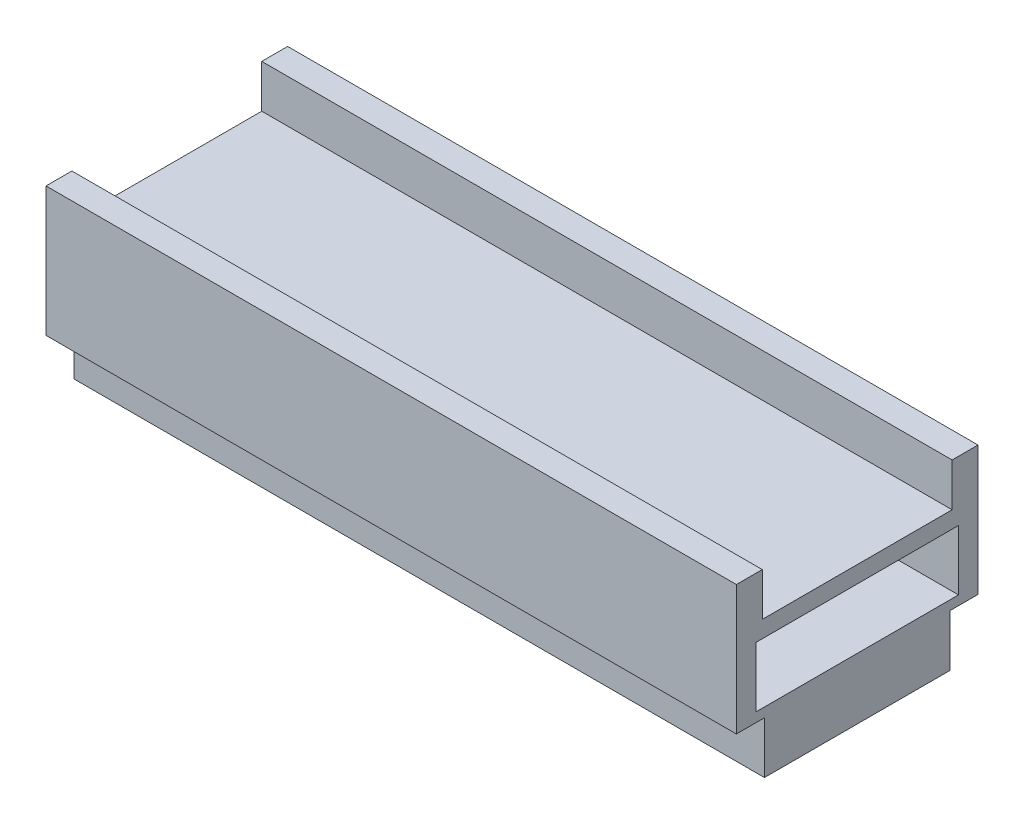
SolidWorks part; units mm, degrees
ref_plane "Front Plane" through (0, 0, 0) normal (0, 0, 1) x (1, 0, 0)
ref_plane "Top Plane" through (0, 0, 0) normal (0, 1, 0) x (1, 0, 0)
ref_plane "Right Plane" through (0, 0, 0) normal (1, 0, 0) x (0, 0, -1)
sketch "Sketch1" plane through (0, 0, 0) normal (0, 1, 0) x (1, 0, 0)
  line L1 (-40, 10.75) -> (40, 10.75)
  line L2 (-40, 10.75) -> (-40, -10.75)
  line L3 (-40, -10.75) -> (40, -10.75)
  line L4 (40, 10.75) -> (40, -10.75)
  line L5 (-40, 10.75) -> (40, -10.75) construction
  line L6 (-40, -10.75) -> (40, 10.75) construction
  point P0 (0, 0)
  dimension "D1" = 21.5
  dimension "D2" = 80
extrude "Boss-Extrude1" add sketch "Sketch1" along normal blind 6
sketch "Sketch2" plane through (0, 6, 0) normal (0, 1, 0) x (1, 0, 0)
  line L1 (-40, 14) -> (40, 14)
  line L2 (-40, 14) -> (-40, -14)
  line L3 (-40, -14) -> (40, -14)
  line L4 (40, 14) -> (40, -14)
  line L5 (-40, 14) -> (40, -14) construction
  line L6 (-40, -14) -> (40, 14) construction
  point P0 (0, 0)
  dimension "D1" = 80
  dimension "D2" = 28
extrude "Boss-Extrude2" add sketch "Sketch2" along normal blind 15
sketch "Sketch3" plane through (0, 21, 0) normal (0, 1, 0) x (1, 0, 0)
  line L0 (40, -14) -> (40, 14) construction
  line L1 (-40, 11) -> (40, 11)
  line L2 (-40, 11) -> (-40, -11)
  line L3 (-40, -11) -> (40, -11)
  line L4 (40, 11) -> (40, -11)
  line L5 (-40, 11) -> (40, -11) construction
  line L6 (-40, -11) -> (40, 11) construction
  point P0 (0, 0)
  dimension "D1" = 22
extrude "Cut-Extrude1" cut sketch "Sketch3" against normal blind 5
sketch "Sketch4" plane through (40, 0, 0) normal (1, 0, 0) x (0, 0, -1)
  line L1 (-11.7434, 14.0541) -> (11.7434, 14.0541)
  line L2 (-11.7434, 14.0541) -> (-11.7434, 7.0853)
  line L3 (-11.7434, 7.0853) -> (11.7434, 7.0853)
  line L4 (11.7434, 14.0541) -> (11.7434, 7.0853)
  line L5 (-11.7434, 14.0541) -> (11.7434, 7.0853) construction
  line L6 (-11.7434, 7.0853) -> (11.7434, 14.0541) construction
  point P0 (0, 10.5697)
  point P1 (0, 10.5697)
extrude "Cut-Extrude2" cut sketch "Sketch4" against normal up to next
